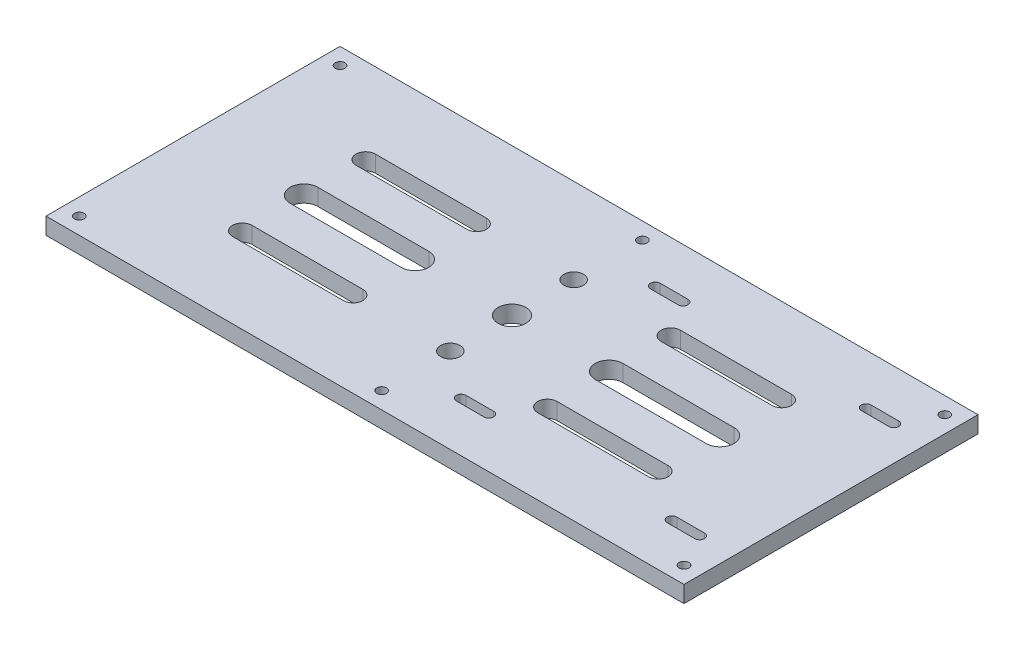
SolidWorks part; units mm, degrees
ref_plane "Front Plane" through (0, 0, 0) normal (0, 0, 1) x (1, 0, 0)
ref_plane "Top Plane" through (0, 0, 0) normal (0, 1, 0) x (1, 0, 0)
ref_plane "Right Plane" through (0, 0, 0) normal (1, 0, 0) x (0, 0, -1)
sketch "Sketch1" plane through (0, 0, 0) normal (0, 1, 0) x (1, 0, 0)
  line L0 (0, 0) -> (0, 22.25) construction
  line L1 (-115, 53) -> (115, 53)
  line L2 (-115, 53) -> (-115, -53)
  line L3 (-115, -53) -> (115, -53)
  line L4 (115, 53) -> (115, -53)
  line L5 (0, 0) -> (-19.3489, 0) construction
  line L6 (0, -5) -> (0, 5) construction
  line L7 (35, 5) -> (75, 5)
  line L9 (35, -5) -> (75, -5)
  line L11 (0, 25.75) -> (0, 18.75) construction
  line L12 (35, 18.75) -> (75, 18.75)
  line L14 (35, 25.75) -> (75, 25.75)
  line L32 (0, 0) -> (59.66, 0) construction
  line L33 (109, 47) -> (115, 47) construction
  line L34 (16.66, -33.25) -> (26.66, -33.25)
  line L35 (16.66, -36.75) -> (26.66, -36.75)
  line L36 (16.66, 36.75) -> (26.66, 36.75)
  line L38 (16.66, 33.25) -> (26.66, 33.25)
  line L39 (59.66, 0) -> (59.66, 13.4787) construction
  line L40 (102.66, -33.25) -> (92.66, -33.25)
  line L41 (102.66, -36.75) -> (92.66, -36.75)
  line L42 (102.66, 33.25) -> (92.66, 33.25)
  line L43 (102.66, 36.75) -> (92.66, 36.75)
  line L44 (35, -18.75) -> (75, -18.75)
  line L45 (35, -25.75) -> (75, -25.75)
  line L46 (-35, 18.75) -> (-75, 18.75)
  line L47 (-35, 25.75) -> (-75, 25.75)
  line L48 (-35, -5) -> (-75, -5)
  line L49 (-35, 5) -> (-75, 5)
  line L50 (-35, -18.75) -> (-75, -18.75)
  line L51 (-35, -25.75) -> (-75, -25.75)
  circle A0 centre (0, 0) radius 5
  circle A1 centre (0, 22.25) radius 3.5
  circle A2 centre (0, -22.25) radius 3.5
  circle A3 centre (109, 47) radius 1.75
  circle A7 centre (109, -47) radius 1.75
  circle A8 centre (-109, -47) radius 1.75
  circle A9 centre (-109, 47) radius 1.75
  arc A10 (35, 18.75) -> (35, 25.75) centre (35, 22.25) cw
  arc A11 (75, 18.75) -> (75, 25.75) centre (75, 22.25) ccw
  arc A12 (75, -5) -> (75, 5) centre (75, 0) ccw
  arc A13 (35, -5) -> (35, 5) centre (35, 0) cw
  arc A14 (26.66, 36.75) -> (26.66, 33.25) centre (26.66, 35) cw
  arc A15 (16.66, 33.25) -> (16.66, 36.75) centre (16.66, 35) cw
  arc A16 (16.66, -33.25) -> (16.66, -36.75) centre (16.66, -35) ccw
  arc A17 (26.66, -36.75) -> (26.66, -33.25) centre (26.66, -35) ccw
  arc A18 (92.66, -36.75) -> (92.66, -33.25) centre (92.66, -35) cw
  arc A19 (102.66, -33.25) -> (102.66, -36.75) centre (102.66, -35) cw
  arc A20 (102.66, 33.25) -> (102.66, 36.75) centre (102.66, 35) ccw
  arc A21 (92.66, 36.75) -> (92.66, 33.25) centre (92.66, 35) ccw
  arc A22 (35, -18.75) -> (35, -25.75) centre (35, -22.25) ccw
  arc A23 (75, -18.75) -> (75, -25.75) centre (75, -22.25) cw
  arc A24 (-35, 18.75) -> (-35, 25.75) centre (-35, 22.25) ccw
  arc A25 (-75, 18.75) -> (-75, 25.75) centre (-75, 22.25) cw
  arc A26 (-35, -5) -> (-35, 5) centre (-35, 0) ccw
  arc A27 (-75, -5) -> (-75, 5) centre (-75, 0) cw
  arc A28 (-75, -18.75) -> (-75, -25.75) centre (-75, -22.25) ccw
  arc A29 (-35, -18.75) -> (-35, -25.75) centre (-35, -22.25) cw
  circle A30 centre (0, 47) radius 1.75
  circle A31 centre (0, -47) radius 1.75
  point P4 (0, 53)
  point P6 (115, 0)
  point P21 (21.66, 36.75)
  point P60 (21.66, 33.25)
  dimension "D3" = 10
  dimension "D5" = 7
  dimension "D9" = 3.5
  dimension "D16" = 1.75
  dimension "D1" = 106
  dimension "D2" = 230
  dimension "D4" = 22.25
  dimension "D6" = 75
  dimension "D7" = 35
  dimension "D8" = 6
  dimension "D10" = 59.66
  dimension "D11" = 35
  dimension "D12" = 38
  dimension "D13" = 10
  dimension "D14" = 3.5
  dimension "D15" = 47
extrude "Boss-Extrude1" add sketch "Sketch1" along normal blind 6
